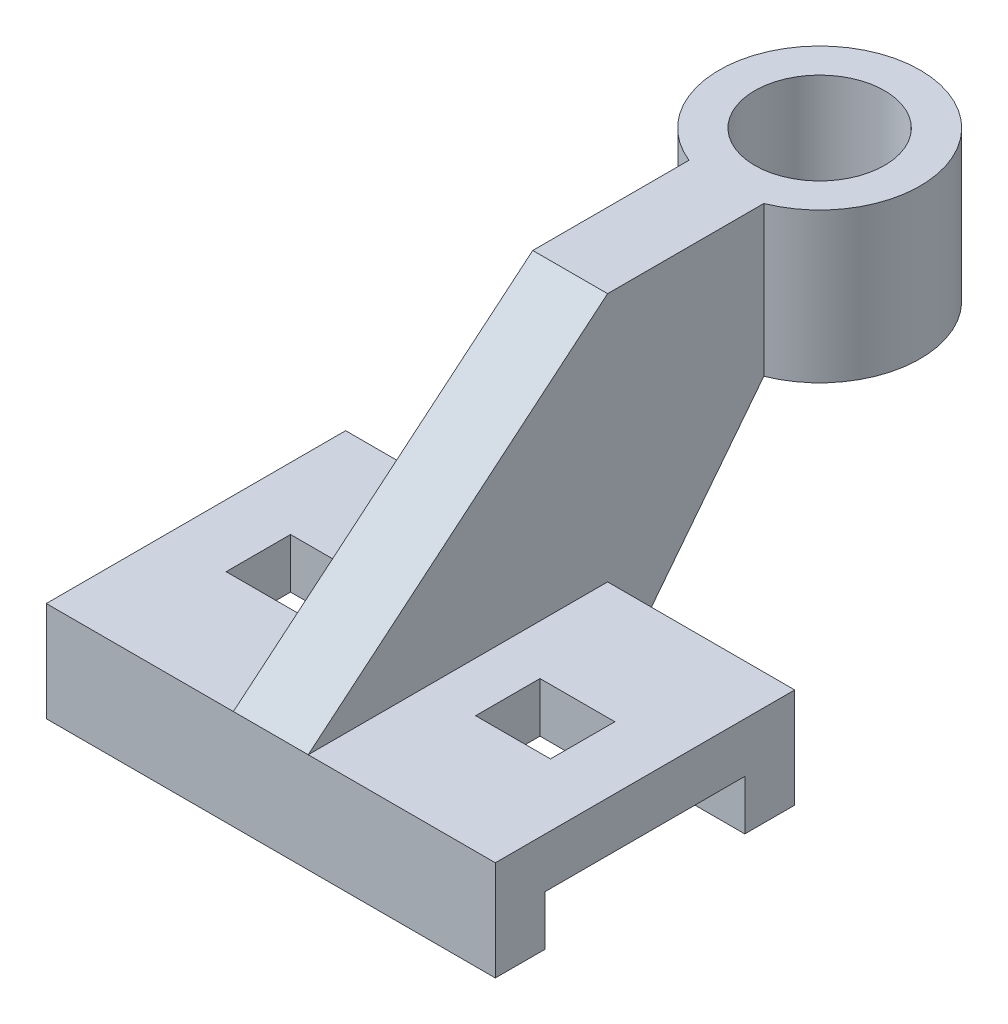
SolidWorks part; units mm, degrees
ref_plane "Front Plane" through (0, 0, 0) normal (0, 0, 1) x (1, 0, 0)
ref_plane "Top Plane" through (0, 0, 0) normal (0, 1, 0) x (1, 0, 0)
ref_plane "Right Plane" through (0, 0, 0) normal (1, 0, 0) x (0, 0, -1)
sketch "Sketch1" plane through (0, 0, 0) normal (0, 0, 1) x (1, 0, 0)
  line L0 (0, 76.4529) -> (0, -69.6204) construction
  line L1 (-120.3927, 0) -> (157.6178, 0) construction
  line L3 (-39.3455, 0) -> (50.6545, 0)
  line L4 (-39.3455, 0) -> (-39.3455, 20)
  line L5 (-39.3455, 20) -> (50.6545, 20)
  line L6 (50.6545, 0) -> (50.6545, 20)
  dimension "D1" = 90
  dimension "D2" = 20
extrude "Boss-Extrude1" add sketch "Sketch1" along normal blind 60
sketch "Sketch2" plane through (50.6545, 0, 0) normal (1, 0, 0) x (0, 0, -1)
  line L0 (-60, 0) -> (0, 0) construction
  line L1 (-50, 0) -> (-10, 0)
  line L2 (-50, 0) -> (-50, 10)
  line L3 (-50, 10) -> (-10, 10)
  line L4 (-10, 0) -> (-10, 10)
  line L5 (-60, 0) -> (-60, 20) construction
  line L6 (0, 11) -> (0, -11) construction
  dimension "D1" = 10
  dimension "D2" = 10
extrude "Cut-Extrude2" cut sketch "Sketch2" against normal blind 90 contours L2 L1 L4 L3
sketch "Sketch3" plane through (0, 20, 0) normal (0, 1, 0) x (1, 0, 0)
  line L6 (5.6545, -1.22) -> (5.6545, -57.4919)
  line L9 (-26.8455, -23.5459) -> (-11.8455, -23.5459)
  line L10 (-26.8455, -23.5459) -> (-26.8455, -36.4541)
  line L11 (-26.8455, -36.4541) -> (-11.8455, -36.4541)
  line L12 (-11.8455, -23.5459) -> (-11.8455, -36.4541)
  line L13 (-26.8455, -23.5459) -> (-11.8455, -36.4541) construction
  line L14 (-26.8455, -36.4541) -> (-11.8455, -23.5459) construction
  line L15 (38.1545, -36.4541) -> (23.1545, -23.5459) construction
  line L16 (38.1545, -23.5459) -> (23.1545, -36.4541) construction
  line L17 (23.1545, -23.5459) -> (23.1545, -36.4541)
  line L18 (38.1545, -36.4541) -> (23.1545, -36.4541)
  line L19 (38.1545, -23.5459) -> (38.1545, -36.4541)
  line L20 (38.1545, -23.5459) -> (23.1545, -23.5459)
  point P8 (-19.3455, -30)
  point P13 (30.6545, -30)
extrude "Cut-Extrude4" cut sketch "Sketch3" against normal blind 30 contours L12 L9 L10 L11 | L19 L20 L17 L18
sketch "Sketch4" plane through (0, 0, 0) normal (0, 0, -1) x (-1, 0, 0)
  line L0 (39.3455, 20) -> (1.8455, 20)
  line L1 (-50.6545, 20) -> (-13.1545, 20)
  line L6 (-50.6545, 20) -> (39.3455, 20) construction
  line L8 (-13.1545, 20) -> (1.8455, 20)
  line L9 (-13.1545, 20) -> (-13.1545, 70.0293)
  line L10 (-13.1545, 70.0293) -> (1.8455, 70.0293)
  line L11 (1.8455, 20) -> (1.8455, 70.0293)
  dimension "D1" = 37.5
  dimension "D2" = 37.5
extrude "Boss-Extrude7" add sketch "Sketch4" against normal blind 60 and the other way blind 10 contours L9 L8 L11 L10
sketch "Sketch13" plane through (-1.8455, 0, 0) normal (-1, 0, 0) x (0, 0, 1)
  line L0 (60, 20) -> (60, 70.0293)
  line L1 (60, 70.0293) -> (0, 70.0293)
  line L2 (-10, 70.0293) -> (60, 70.0293) construction
  line L3 (0, 70.0293) -> (60, 20)
extrude "Cut-Extrude7" cut sketch "Sketch13" against normal blind 15 contours L3 L0 L1
sketch "Sketch15" plane through (0, 70.0293, 0) normal (0, 1, 0) x (1, 0, 0)
  line L2 (-1.8455, 10) -> (13.1545, 10)
  line L3 (-1.8455, 10) -> (-1.8455, 31.3121)
  line L5 (13.1545, 10) -> (13.1545, 31.3121)
  arc A0 (13.1545, 31.3121) -> (-1.8455, 31.3121) centre (5.6545, 50) ccw
  circle A1 centre (5.6545, 50) radius 13
extrude "Boss-Extrude9" add sketch "Sketch15" against normal blind 30
sketch "Sketch28" plane through (0, 0, 0) normal (0, -1, 0) x (1, 0, 0)
  line L1 (-1.8455, 0) -> (13.1545, 0)
  line L2 (-1.8455, 0) -> (-1.8455, -31.3121)
  line L3 (-1.8455, -31.3121) -> (13.1545, -31.3121)
  line L4 (13.1545, 0) -> (13.1545, -31.3121)
extrude "Boss-Extrude12" add sketch "Sketch28" against normal blind 47 contours L2 L1 L4 L3
sketch "Sketch29" plane through (13.1545, 0, 0) normal (1, 0, 0) x (0, 0, -1)
  line L0 (31.3121, 40.0293) -> (0, 0)
  line L1 (0, 0) -> (31.3121, 0)
  line L2 (31.3121, 0) -> (31.3121, 40.0293)
extrude "Cut-Extrude10" cut sketch "Sketch29" against normal blind 15
